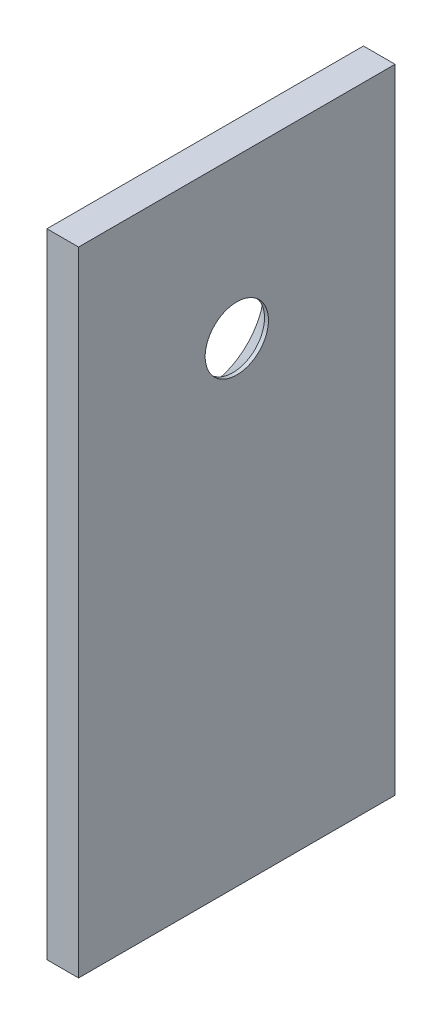
SolidWorks part; units mm, degrees
ref_plane "Front Plane" through (0, 0, 0) normal (0, 0, 1) x (1, 0, 0)
ref_plane "Top Plane" through (0, 0, 0) normal (0, 1, 0) x (1, 0, 0)
ref_plane "Right Plane" through (0, 0, 0) normal (1, 0, 0) x (0, 0, -1)
sketch "Sketch1" plane through (0, 0, 0) normal (1, 0, 0) x (0, 0, -1)
  line L0 (0, -42.5) -> (0, -66.5) construction
  line L1 (-20, -42.5) -> (20, -42.5)
  line L2 (-20, -42.5) -> (-20, -122.5)
  line L3 (-20, -122.5) -> (20, -122.5)
  line L4 (20, -42.5) -> (20, -122.5)
  circle A0 centre (0, -62.5) radius 4
  point P0 (0, 0)
  dimension "D3" = 80
  dimension "D1" = 20
  dimension "D2" = 40
  dimension "D7" = 20
extrude "Boss-Extrude1" add sketch "Sketch1" along normal blind 4
chamfer "Chamfer1" distance 3.5 angle 45 1 edges at (0, -62.5, -4)
